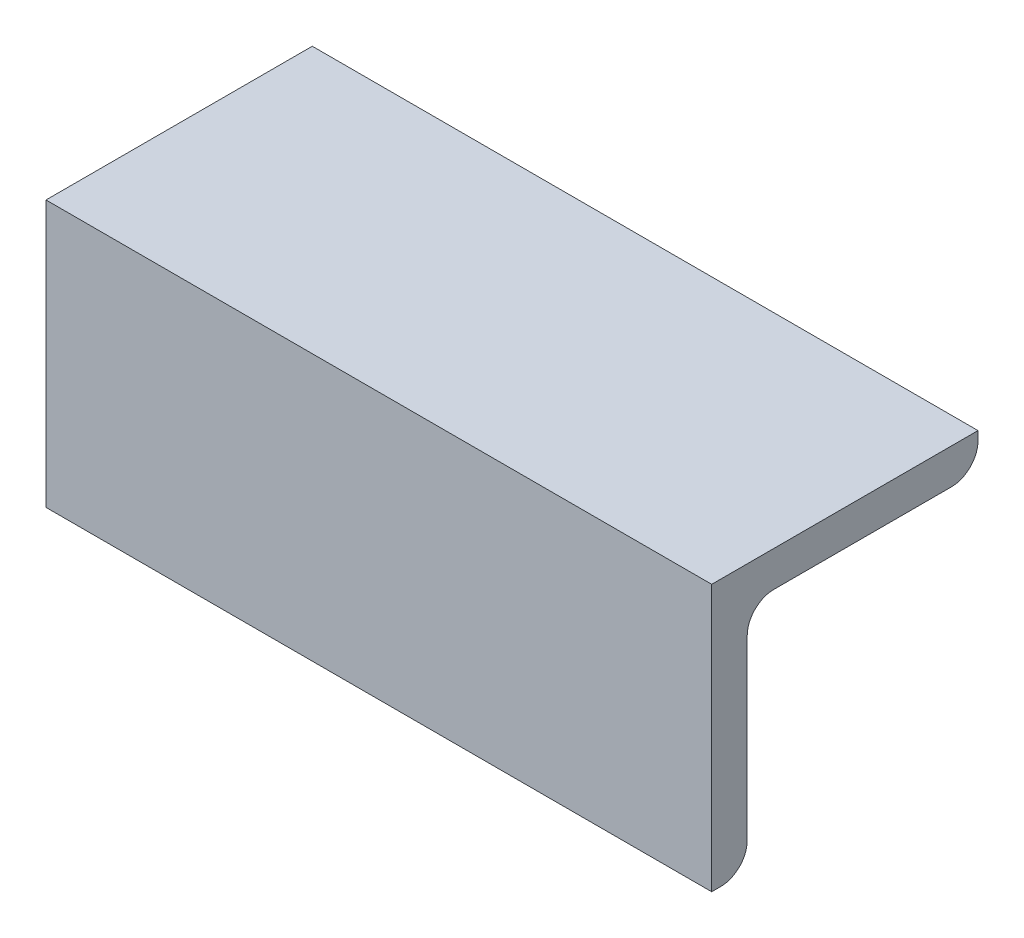
SolidWorks part; units mm, degrees
material "ASTM A36 Steel"
ref_plane "Front Plane" through (0, 0, 0) normal (0, 0, 1) x (1, 0, 0)
ref_plane "Top Plane" through (0, 0, 0) normal (0, 1, 0) x (1, 0, 0)
ref_plane "Right Plane" through (0, 0, 0) normal (1, 0, 0) x (0, 0, -1)
sketch "Sketch1" plane through (0, 0, 0) normal (1, 0, 0) x (0, 0, -1)
  line L0 (0, 16.2896) -> (-30, 16.2896)
  line L1 (-30, 16.2896) -> (-30, -13.7104)
  line L2 (-30, -13.7104) -> (-29, -13.7104)
  line L3 (-26, -10.7104) -> (-26, 9.2896)
  line L4 (-23, 12.2896) -> (-3, 12.2896)
  line L5 (0, 15.2896) -> (0, 16.2896)
  arc A0 (-29, -13.7104) -> (-26, -10.7104) centre (-29, -10.7104) ccw
  arc A1 (-26, 9.2896) -> (-23, 12.2896) centre (-23, 9.2896) cw
  arc A2 (-3, 12.2896) -> (0, 15.2896) centre (-3, 15.2896) ccw
  point P8 (-26, -13.7104)
  point P13 (0, 12.2896)
  dimension "D5" = 3
  dimension "D1" = 30
  dimension "D2" = 30
  dimension "D3" = 4
  dimension "D4" = 4
extrude "Boss-Extrude1" add sketch "Sketch1" along normal blind 75
